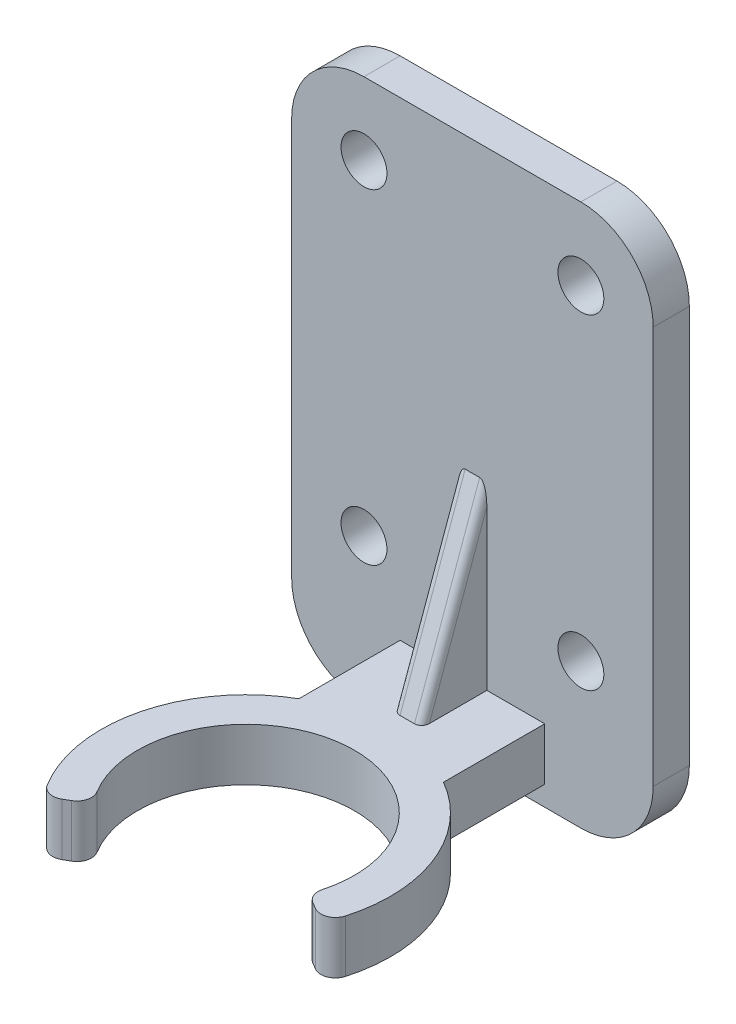
SolidWorks part; units mm, degrees
ref_plane "Front Plane" through (0, 0, 0) normal (0, 0, 1) x (1, 0, 0)
ref_plane "Top Plane" through (0, 0, 0) normal (0, 1, 0) x (1, 0, 0)
ref_plane "Right Plane" through (0, 0, 0) normal (1, 0, 0) x (0, 0, -1)
sketch "Sketch1" plane through (0, 0, 0) normal (0, 1, 0) x (1, 0, 0)
  line L0 (-13.5091, -10.5914) -> (-14.3753, -11.0915)
  line L2 (16.3092, -6.671) -> (15.4147, -6.1546)
  line L4 (0, 0) -> (0, 15) construction
  line L5 (2.6872, 21.3205) -> (-10, 21.3205)
  line L8 (10, 17.3205) -> (10, 21.3205)
  line L9 (10, 21.3205) -> (2.6872, 21.3205)
  line L10 (-10, 17.3205) -> (-10, 21.3205)
  arc A0 (14.4835, -3.9022) -> (-12.8021, -7.817) centre (0, 0) ccw
  arc A1 (19.2324, -5.4877) -> (10, 17.3205) centre (0, 0) ccw
  circle A2 centre (0, 0) radius 20 construction
  circle A3 centre (0, 0) radius 15 construction
  arc A4 (19.2324, -5.4877) -> (16.3092, -6.671) centre (17.3092, -4.939) cw
  arc A5 (15.4147, -6.1546) -> (14.4835, -3.9022) centre (16.4147, -4.4225) cw
  arc A6 (-17.0837, -10.3994) -> (-14.3753, -11.0915) centre (-15.3753, -9.3595) ccw
  arc A7 (-12.8021, -7.817) -> (-13.5091, -10.5914) centre (-14.5091, -8.8593) cw
  arc A8 (-10, 17.3205) -> (-17.0837, -10.3994) centre (0, 0) ccw
  dimension "D1" = 30
  dimension "D4" = 2
  dimension "D3" = 120
  dimension "D5" = 120
  dimension "D6" = 10
  dimension "D7" = 4
  dimension "D8" = 20
  dimension "D9" = 4
  dimension "D2" = 5
extrude "Boss-Extrude1" add sketch "Sketch1" along normal blind 10
sketch "Sketch2" plane through (0, 0, -21.3205) normal (0, 0, -1) x (-1, 0, 0)
  line L1 (-10, 0) -> (10, 0)
  line L2 (-10, 0) -> (-10, 10)
  line L3 (-10, 10) -> (10, 10)
  line L4 (10, 0) -> (10, 10)
extrude "Boss-Extrude2" add sketch "Sketch2" along normal blind 10
ref_plane "Plane2" through (0, 0, -31.3205) normal (0, 0, -1) x (-1, 0, 0)
sketch "Sketch3" plane through (0, 0, -31.3205) normal (0, 0, -1) x (-1, 0, 0)
  line L1 (-15, 75) -> (15, 75)
  line L2 (-25, 65) -> (-25, 10)
  line L3 (-15, 0) -> (15, 0)
  line L4 (25, 65) -> (25, 10)
  arc A0 (-15, 0) -> (-25, 10) centre (-15, 10) cw
  arc A1 (15, 0) -> (25, 10) centre (15, 10) ccw
  arc A2 (-25, 65) -> (-15, 75) centre (-15, 65) cw
  arc A3 (25, 65) -> (15, 75) centre (15, 65) ccw
  dimension "D5" = 10
  dimension "D1" = 25
  dimension "D2" = 25
  dimension "D3" = 0
  dimension "D4" = 75
extrude "Boss-Extrude3" add sketch "Sketch3" along normal blind 5
ref_plane "Plane3" through (0, 0, 0) normal (-1, 0, 0) x (0, 0, 1)
sketch "Sketch4" plane through (0, 0, 0) normal (-1, 0, 0) x (0, 0, 1)
  line L0 (-22.3111, 10) -> (-31.3205, 35)
  line L1 (-31.3205, 10) -> (-17.3205, 10) construction
  line L2 (-31.3205, 55) -> (-31.3205, -55) construction
  line L3 (-31.3205, 35) -> (-31.3205, 10)
  line L4 (-36.3205, 10) -> (-31.3205, 10) construction
  line L5 (-31.3205, 10) -> (-22.3111, 10)
  dimension "D1" = 25
extrude "Boss-Extrude4" add sketch "Sketch4" along normal blind 2 and the other way blind 2
fillet "Fillet1" radius 1 2 edges at (2, 22.5, -26.8158) (-2, 22.5, -26.8158)
sketch "Sketch6" plane through (0, 0, -31.3205) normal (0, 0, 1) x (1, 0, 0)
  line L0 (-15, 75) -> (15, 75) construction
  line L1 (-25, 10) -> (-25, 65) construction
  line L2 (25, 65) -> (25, 10) construction
  circle A0 centre (-15, 65) radius 3.175
  circle A1 centre (15, 65) radius 3.175
  circle A2 centre (15, 20) radius 3.175
  circle A3 centre (-15, 20) radius 3.175
  dimension "D1" = 6.35
  dimension "D2" = 6.35
  dimension "D3" = 6.35
  dimension "D4" = 6.35
  dimension "D5" = 10
  dimension "D6" = 10
  dimension "D7" = 10
  dimension "D8" = 10
  dimension "D9" = 10
  dimension "D10" = 10
  dimension "D11" = 10
  dimension "D12" = 10
extrude "Cut-Extrude1" cut sketch "Sketch6" against normal through all
sketch "Sketch8" plane through (0, 0, 0) normal (0, -1, 0) x (1, 0, 0)
  line L0 (-55, -31.3205) -> (55, -31.3205) construction
  line L1 (-28.5135, -31.3205) -> (26.9671, -31.3205)
  line L2 (-28.5135, -31.3205) -> (-28.5135, 17.2413)
  line L3 (-28.5135, 17.2413) -> (26.9671, 17.2413)
  line L4 (26.9671, -31.3205) -> (26.9671, 17.2413)
extrude "Cut-Extrude2" cut sketch "Sketch8" against normal blind 2.75
